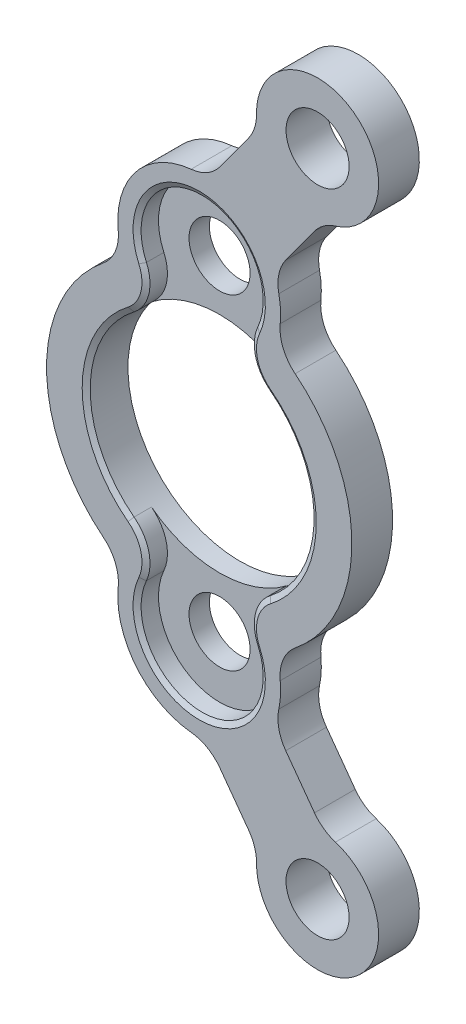
SolidWorks part; units mm, degrees
material "2018 合金"
ref_plane "正面" through (0, 0, 0) normal (0, 0, 1) x (1, 0, 0)
ref_plane "平面" through (0, 0, 0) normal (0, 1, 0) x (1, 0, 0)
ref_plane "右側面" through (0, 0, 0) normal (1, 0, 0) x (0, 0, -1)
sketch "ｽｹｯﾁ1" plane through (0, 0, 0) normal (0, 0, 1) x (1, 0, 0)
  line L0 (0, 0) -> (5.5, 0) construction
  line L1 (5.8143, 15.9748) -> (0, 0) construction
  circle A0 centre (0, 0) radius 5.5
  circle A1 centre (0, -8) radius 1.5
  circle A2 centre (0, 8) radius 1.5
  circle A4 centre (0, 0) radius 14 construction
  circle A5 centre (5.8143, 15.9748) radius 3
  circle A6 centre (5.8143, 15.9748) radius 1.55
  circle A7 centre (5.8143, -15.9748) radius 3
  circle A8 centre (5.8143, -15.9748) radius 1.55
  arc A9 (3.7144, -6.5156) -> (3.7144, 6.5156) centre (0, 0) ccw
  arc A10 (-3.7144, 6.5156) -> (-3.7144, -6.5156) centre (0, 0) ccw
  arc A11 (3.7144, -6.5156) -> (-3.7144, -6.5156) centre (0, -8) cw
  arc A12 (3.7144, 6.5156) -> (-3.7144, 6.5156) centre (0, 8) ccw
  dimension "D1" = 11
  dimension "D2" = 3
  dimension "D3" = 6
  dimension "D5" = 3.1
  dimension "D6" = 4
  dimension "D7" = 15
  dimension "D8" = 28
  dimension "D4" = 70
extrude "ﾎﾞｽ - 押し出し1" add sketch "ｽｹｯﾁ1" along normal blind 2
sketch "ｽｹｯﾁ2" plane through (0, 0, 2) normal (0, 0, 1) x (1, 0, 0)
  line L0 (0, 8) -> (5.8143, 15.9748) construction
  line L1 (1.6161, 6.8217) -> (7.4304, 14.7965)
  line L2 (-1.6161, 9.1783) -> (4.1983, 17.153)
  line L3 (0, 0) -> (7.5, 0) construction
  line L4 (0, -8) -> (5.8143, -15.9748) construction
  line L5 (-1.6161, -9.1783) -> (4.1983, -17.153)
  line L6 (1.6161, -6.8217) -> (7.4304, -14.7965)
  circle A0 centre (5.8143, 15.9748) radius 3 construction
  arc A1 (3.7144, 6.5156) -> (-3.7144, 6.5156) centre (0, 8) ccw construction
  circle A2 centre (5.8143, 15.9748) radius 3
  arc A3 (3.7144, 6.5156) -> (-3.7144, 6.5156) centre (0, 8) ccw
  arc A4 (3.7144, -6.5156) -> (3.7144, 6.5156) centre (0, 0) ccw construction
  arc A5 (3.7144, -6.5156) -> (-3.7144, -6.5156) centre (0, -8) cw
  circle A6 centre (5.8143, -15.9748) radius 3
  arc M3 (3.7144, 6.5156) -> (-3.7144, 6.5156) centre (0, 8) ccw
  arc M5 (-3.7144, -6.5156) -> (3.7144, -6.5156) centre (0, -8) ccw
  dimension "D1" = 2
  dimension "D2" = 2
extrude "ﾎﾞｽ - 押し出し2" add sketch "ｽｹｯﾁ2" against normal through all contours L0 L1 A2 M3 | A3 L0 A2 L2 | L5 A6 L6 M5
sketch "ｽｹｯﾁ3" plane through (0, 0, 2) normal (0, 0, 1) x (1, 0, 0)
  line L0 (-7.5, 0) -> (7.5, 0) construction
  circle A0 centre (0, 8) radius 3
  arc A1 (-3.7144, 6.5156) -> (-3.7144, -6.5156) centre (0, 0) ccw construction
  arc A2 (3.7144, -6.5156) -> (3.7144, 6.5156) centre (0, 0) ccw construction
  circle A3 centre (0, -8) radius 3
  dimension "D1" = 6
extrude "ｶｯﾄ - 押し出し1" cut sketch "ｽｹｯﾁ3" against normal blind 1
fillet "ﾌｨﾚｯﾄ2" radius 2 16 edges at (6.1131, 12.9897, 1) (2.8809, 15.3462, 1) (0.4247, 11.9774, 1) (-3.7144, 6.5156, 1) (-3.7144, -6.5156, 1) (0.4247, -11.9774, 1) (2.8809, -15.3462, 1) (6.1131, -12.9897, 1) (3.6569, -9.6209, 1) (3.7144, -6.5156, 1) (3.7144, 6.5156, 1) (3.6569, 9.6209, 1) (-1.3642, -5.3281, 1.5) (1.3642, -5.3281, 1.5) (1.3642, 5.3281, 1.5) (-1.3642, 5.3281, 1.5)
chamfer "面取り1" distance 0.25 angle 30 8 edges at (0, -11, 2) (2.6228, -5.463, 2) (-2.6228, -5.463, 2) (5.5, 0, 2) (-5.5, 0, 2) (2.6228, 5.463, 2) (-2.6228, 5.463, 2) (0, 11, 2)
sketch "ｽｹｯﾁ4" plane through (0, 0, 0) normal (0, 0, -1) x (-1, 0, 0)
  line L8 (-6.1339, -9.1991) -> (-7.4327, -10.9804)
  line L9 (-0.5644, -15.9881) -> (0.7344, -14.2067)
  line L10 (0.7344, 14.2067) -> (-0.5644, 15.9881)
  line L11 (-7.4327, 10.9804) -> (-6.1339, 9.1991)
  line L12 (-6.1339, -9.1991) -> (-7.4327, -10.9804)
  line L13 (-0.5644, -15.9881) -> (0.7344, -14.2067)
  line L14 (0.7344, 14.2067) -> (-0.5644, 15.9881)
  line L15 (-7.4327, 10.9804) -> (-6.1339, 9.1991)
  arc A40 (-6.1339, 9.1991) -> (-6.23, 7.5) centre (0, 8) ccw
  arc A41 (-6.23, 7.5) -> (-6.23, -7.5) centre (0, 0) ccw
  arc A42 (-6.23, -7.5) -> (-6.1339, -9.1991) centre (0, -8) ccw
  arc A43 (-7.4327, -10.9804) -> (-0.5644, -15.9881) centre (-5.8143, -15.9748) ccw
  arc A44 (0.7344, -14.2067) -> (6.23, -7.5) centre (0, -8) ccw
  arc A45 (6.23, -7.5) -> (6.23, 7.5) centre (0, 0) ccw
  arc A46 (6.23, 7.5) -> (0.7344, 14.2067) centre (0, 8) ccw
  arc A47 (-0.5644, 15.9881) -> (-7.4327, 10.9804) centre (-5.8143, 15.9748) ccw
  arc A48 (-6.1339, 9.1991) -> (-6.23, 7.5) centre (0, 8) ccw
  arc A49 (-6.23, 7.5) -> (-6.23, -7.5) centre (0, 0) ccw
  arc A50 (-6.23, -7.5) -> (-6.1339, -9.1991) centre (0, -8) ccw
  arc A51 (-7.4327, -10.9804) -> (-0.5644, -15.9881) centre (-5.8143, -15.9748) ccw
  arc A52 (0.7344, -14.2067) -> (6.23, -7.5) centre (0, -8) ccw
  arc A53 (6.23, -7.5) -> (6.23, 7.5) centre (0, 0) ccw
  arc A54 (6.23, 7.5) -> (0.7344, 14.2067) centre (0, 8) ccw
  arc A55 (-0.5644, 15.9881) -> (-7.4327, 10.9804) centre (-5.8143, 15.9748) ccw
  dimension "D1" = 2.25
